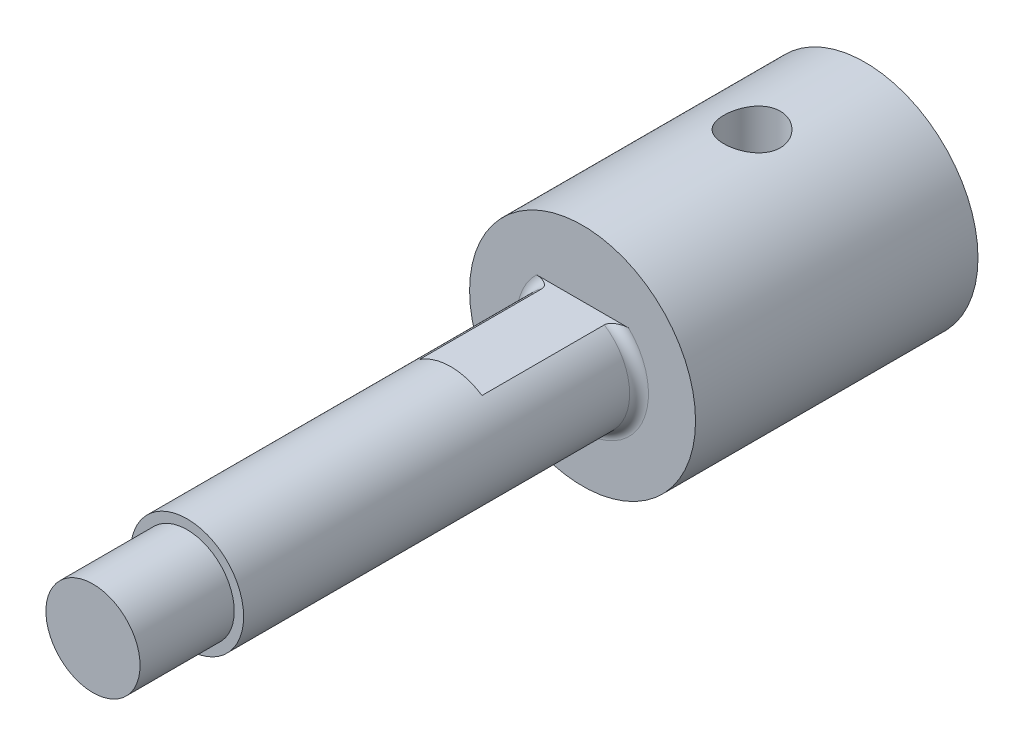
SolidWorks part; units mm, degrees
ref_plane "Front Plane" through (0, 0, 0) normal (0, 0, 1) x (1, 0, 0)
ref_plane "Top Plane" through (0, 0, 0) normal (0, 1, 0) x (1, 0, 0)
ref_plane "Right Plane" through (0, 0, 0) normal (1, 0, 0) x (0, 0, -1)
sketch "Sketch1" plane through (0, 0, 0) normal (0, 0, 1) x (1, 0, 0)
  circle A0 centre (0, 0) radius 6
  circle A3 centre (0, 0) radius 3
  dimension "D1" = 6
  dimension "D3" = 12
extrude "Boss-Extrude1" add sketch "Sketch1" along normal blind 11
sketch "Sketch2" plane through (0, 0, 0) normal (0, 1, 0) x (1, 0, 0)
  circle A0 centre (0, -6) radius 1.5
  dimension "D1" = 3
  dimension "D2" = 6
extrude "Cut-Extrude1" cut sketch "Sketch2" along normal through all
sketch "Sketch3" plane through (0, 0, 11) normal (0, 0, 1) x (1, 0, 0)
  circle A0 centre (0, 0) radius 6
  circle A1 centre (0, 0) radius 6 construction
extrude "Boss-Extrude2" add sketch "Sketch3" along normal blind 4
sketch "Sketch4" plane through (0, 0, 15) normal (0, 0, 1) x (1, 0, 0)
  line L0 (-1.6583, 2.5) -> (1.6583, 2.5)
  arc A1 (-1.6583, 2.5) -> (1.6583, 2.5) centre (0, 0) ccw
  point P5 (0, 2.5)
  dimension "D1" = 3
  dimension "D2" = 2.5
extrude "Boss-Extrude3" add sketch "Sketch4" along normal blind 7
sketch "Sketch5" plane through (0, 0, 22) normal (0, 0, 1) x (1, 0, 0)
  circle A0 centre (0, 0) radius 3
  arc A1 (-1.6583, 2.5) -> (1.6583, 2.5) centre (0, 0) ccw construction
extrude "Boss-Extrude6" add sketch "Sketch5" along normal blind 14
sketch "Sketch7" plane through (0, 0, 36) normal (0, 0, 1) x (1, 0, 0)
  circle A0 centre (0, 0) radius 2.5
  dimension "D1" = 5
extrude "Boss-Extrude7" add sketch "Sketch7" along normal blind 5
fillet "Fillet1" radius 0.5 1 edges at (0, -3, 15)
